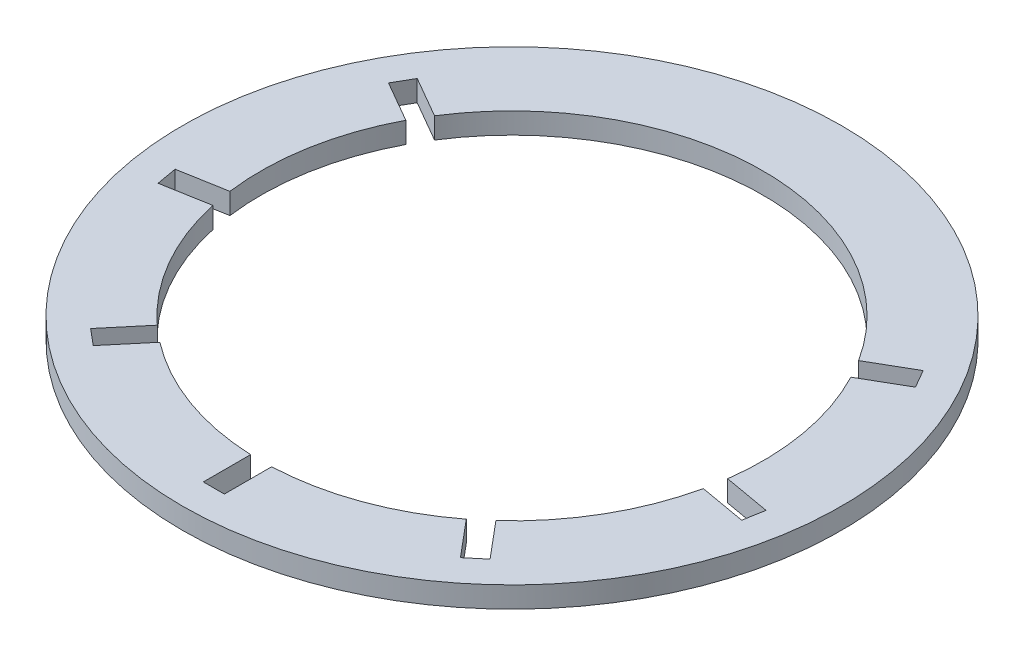
SolidWorks part; units mm, degrees
material "Balsa"
ref_plane "Front Plane" through (0, 0, 0) normal (0, 0, 1) x (1, 0, 0)
ref_plane "Top Plane" through (0, 0, 0) normal (0, 1, 0) x (1, 0, 0)
ref_plane "Right Plane" through (0, 0, 0) normal (1, 0, 0) x (0, 0, -1)
sketch "Sketch1" plane through (0, 0, 0) normal (0, 1, 0) x (1, 0, 0)
  circle A0 centre (0, 0) radius 105
  circle A1 centre (0, 0) radius 80
  dimension "D1" = 105
  dimension "D2" = 80
extrude "Boss-Extrude1" add sketch "Sketch1" along normal blind 6.7 contours A0
sketch "Sketch2" plane through (0, 6.7, 0) normal (0, 1, 0) x (1, 0, 0)
  line L0 (0, 0) -> (90.9327, 52.5) construction
  line L2 (63.2769, 40.4012) -> (80.5974, 50.4012)
  line L3 (63.2769, 40.4012) -> (66.6269, 34.5988)
  line L4 (66.6269, 34.5988) -> (83.9474, 44.5988)
  line L5 (80.5974, 50.4012) -> (83.9474, 44.5988)
  line L9 (50.7753, -55.3) -> (63.6311, -70.6209)
  line L10 (50.7753, -55.3) -> (45.6428, -59.6067)
  line L11 (45.6428, -59.6067) -> (58.4986, -74.9276)
  line L12 (63.6311, -70.6209) -> (58.4986, -74.9276)
  line L16 (74.4423, -9.7245) -> (94.1385, -13.1975)
  line L17 (74.4423, -9.7245) -> (73.2789, -16.3227)
  line L18 (73.2789, -16.3227) -> (92.975, -19.7957)
  line L19 (94.1385, -13.1975) -> (92.975, -19.7957)
  line L23 (0, 0) -> (67.4927, -80.4347) construction
  line L25 (3.35, -75) -> (3.35, -95)
  line L26 (3.35, -75) -> (-3.35, -75)
  line L29 (0, 0) -> (103.4048, -18.2331) construction
  line L30 (-3.35, -75) -> (-3.35, -95)
  line L31 (3.35, -95) -> (-3.35, -95)
  line L34 (0, 0) -> (0, -105) construction
  line L36 (-45.6428, -59.6067) -> (-58.4986, -74.9276)
  line L37 (-45.6428, -59.6067) -> (-50.7753, -55.3)
  line L38 (-50.7753, -55.3) -> (-63.6311, -70.6209)
  line L39 (-58.4986, -74.9276) -> (-63.6311, -70.6209)
  line L42 (0, 0) -> (-67.4927, -80.4347) construction
  line L44 (-73.2789, -16.3227) -> (-92.975, -19.7957)
  line L45 (-73.2789, -16.3227) -> (-74.4423, -9.7245)
  line L46 (-74.4423, -9.7245) -> (-94.1385, -13.1975)
  line L47 (-92.975, -19.7957) -> (-94.1385, -13.1975)
  line L50 (0, 0) -> (-103.4048, -18.2331) construction
  line L55 (-66.6269, 34.5988) -> (-83.9474, 44.5988)
  line L56 (-66.6269, 34.5988) -> (-63.2769, 40.4012)
  line L57 (-63.2769, 40.4012) -> (-80.5974, 50.4012)
  line L58 (-83.9474, 44.5988) -> (-80.5974, 50.4012)
  line L61 (0, 0) -> (-90.9327, 52.5) construction
  line L63 (0, 0) -> (0, 102.8222) construction
  circle A0 centre (0, 0) radius 105 construction
  circle A1 centre (0, -10) radius 3.5
  point P13 (-12.0777, 27.2748)
  point P71 (-3.8455, -6.6605)
  point P72 (-4.6778, -8.1021)
  point P73 (0, 0)
  point P75 (64.9519, 37.5)
  dimension "D9" = 7
  dimension "D1" = 20
  dimension "D2" = 6.7
  dimension "D3" = 3.35
  dimension "D6" = 40
  dimension "D10" = 10
  dimension "D4" = 75
  dimension "D7" = 7
extrude "Cut-Extrude3" cut sketch "Sketch2" against normal blind 6.7
equation "\"Ring inner radius\" = 80mm"
equation "\"D1@Sketch1\" = \"Ring outer radius\""
equation "\"Heart cable hole radius\"= 3.5mm"
equation "\"Dogbone radius\"= 3mm"
equation "\"Tree side stock thickness\"= 6.7mm"
equation "\"D2@Sketch2\"= \"Tree side stock thickness\""
equation "\"D3@Sketch2\"= \"Tree side stock thickness\" / 2"
equation "\"Ring stock thickness\" = 6.7mm"
equation "\"D1@Boss-Extrude1\"= \"Ring stock thickness\""
equation "\"D1@Cut-Extrude3\"= \"Ring stock thickness\""
equation "\"Tree teeth\" = 15mm"
equation "\"Tree slot\"= 15mm"
equation "\"D1@Sketch2\"= \"Tree slot\" + \"Cut-Extrude Tolerance\""
equation "\"Bottom ring outer radius\" = \"Ring inner radius\" + \"Tree teeth\""
equation "\"D4@Sketch2\" = \"Ring inner radius\" - \"Cut-Extrude Tolerance\""
equation "\"D9@Sketch2\" = \"Heart cable hole radius\" * 2"
equation "\"Cut-Extrude Tolerance\"= 5mm"
equation "\"Ring outer radius\"= \"Ring inner radius\" + \"Tree slot\" + 10"
equation "\"D2@Sketch1\"= \"Ring inner radius\""
